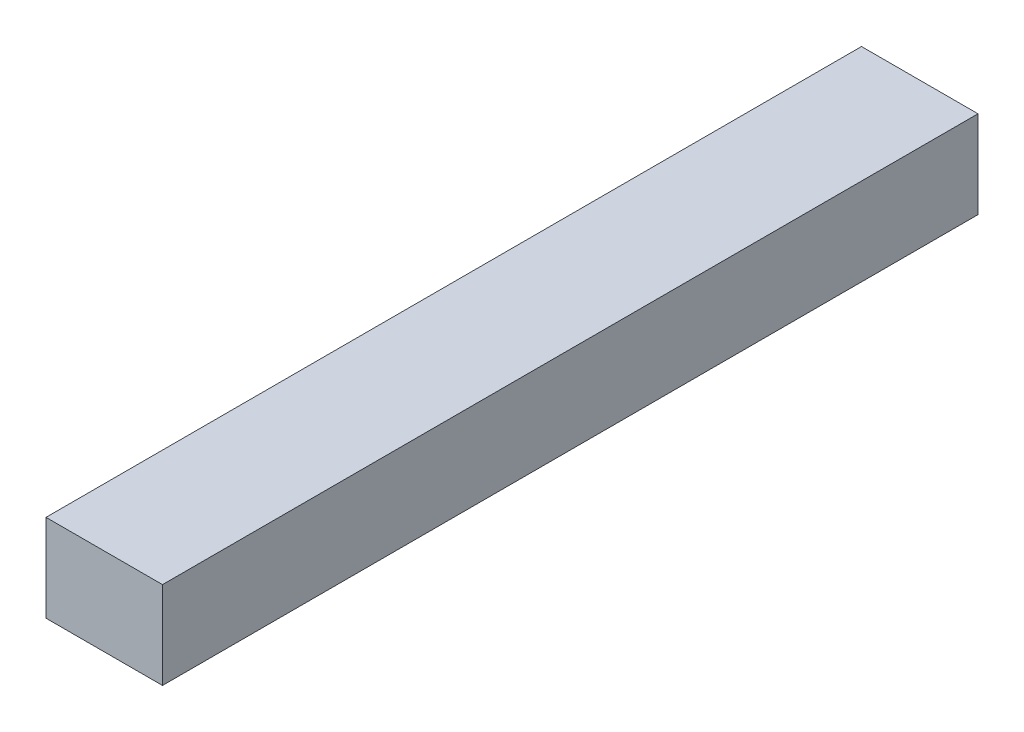
SolidWorks part; units mm, degrees
ref_plane "Front Plane" through (0, 0, 0) normal (0, 0, 1) x (1, 0, 0)
ref_plane "Top Plane" through (0, 0, 0) normal (0, 1, 0) x (1, 0, 0)
ref_plane "Right Plane" through (0, 0, 0) normal (1, 0, 0) x (0, 0, -1)
sketch "Sketch2" plane through (0, 0, 0) normal (1, 0, 0) x (0, 0, -1)
  line L1 (0, 0) -> (177.8, 0)
  line L2 (0, 0) -> (0, 19.05)
  line L3 (0, 19.05) -> (177.8, 19.05)
  line L4 (177.8, 0) -> (177.8, 19.05)
  line L5 (0, 0) -> (177.8, 19.05) construction
  line L6 (0, 19.05) -> (177.8, 0) construction
  point P4 (88.9, 9.525)
  dimension "D1" = 19.05
  dimension "D2" = 177.8
extrude "Boss-Extrude1" add sketch "Sketch2" along normal blind 25.4
